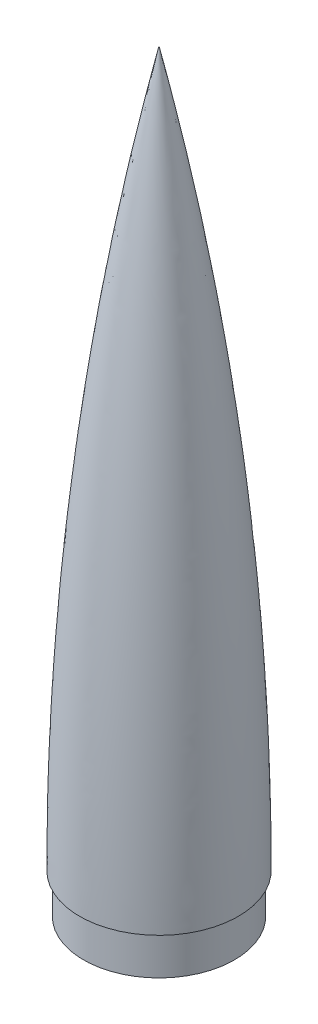
SolidWorks part; units mm, degrees
material "Polyurethane Foam Rigid"
ref_plane "Front Plane" through (0, 0, 0) normal (0, 0, 1) x (1, 0, 0)
ref_plane "Top Plane" through (0, 0, 0) normal (0, 1, 0) x (1, 0, 0)
ref_plane "Right Plane" through (0, 0, 0) normal (1, 0, 0) x (0, 0, -1)
sketch "Sketch1" plane through (0, 0, 0) normal (0, 0, 1) x (1, 0, 0)
  line L0 (0, 0) -> (0, 228.6) construction
  line L1 (-25.4, 0) -> (1016, 0) construction
  line L2 (-25.4, 0) -> (-24.1554, 0)
  line L3 (-24.1554, 0) -> (-24.1554, -12.7)
  line L4 (-24.1554, -12.7) -> (0, -12.7)
  line L6 (0, -12.7) -> (0, 228.6)
  arc A0 (-25.4, 0) -> (0, 228.6) centre (1016, 0) cw
  dimension "D1" = 50.8
  dimension "D2" = 228.6
  dimension "D3" = 48.3108
  dimension "D4" = 12.7
revolve "Revolve1" add sketch "Sketch1" angle 360 about L6
